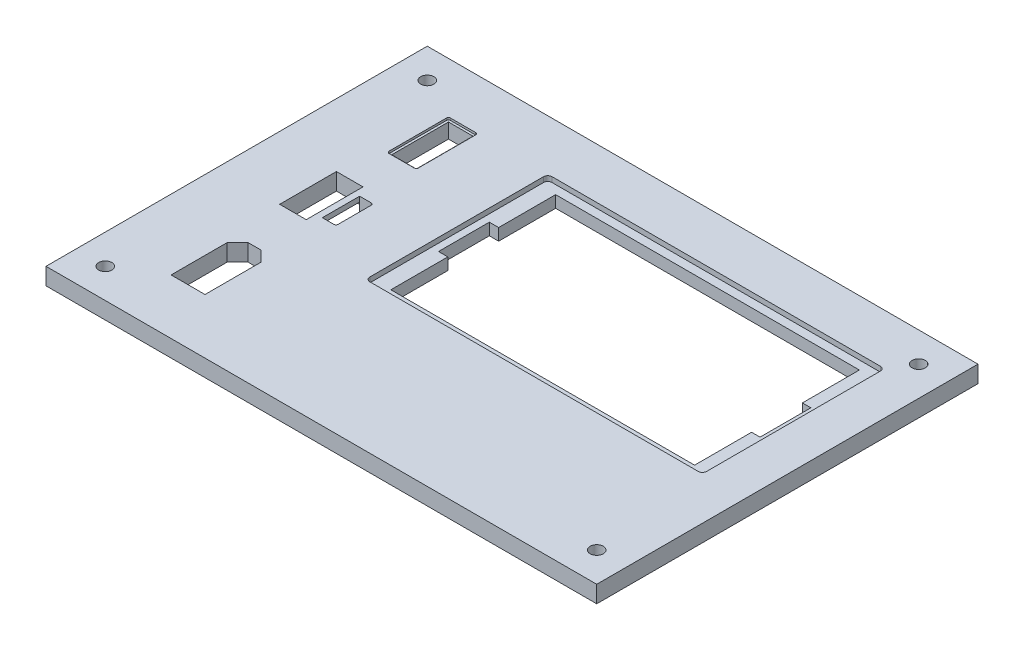
SolidWorks part; units mm, degrees
ref_plane "Спереди" through (0, 0, 0) normal (0, 0, 1) x (1, 0, 0)
ref_plane "Сверху" through (0, 0, 0) normal (0, 1, 0) x (1, 0, 0)
ref_plane "Справа" through (0, 0, 0) normal (1, 0, 0) x (0, 0, -1)
sketch "Эскиз1" plane through (0, 0, 0) normal (0, 1, 0) x (1, 0, 0)
  line L1 (-65, 45) -> (65, 45)
  line L2 (-65, 45) -> (-65, -45)
  line L3 (-65, -45) -> (65, -45)
  line L4 (65, 45) -> (65, -45)
  line L5 (-65, 45) -> (65, -45) construction
  line L6 (-65, -45) -> (65, 45) construction
  line L7 (-20.7, 31) -> (51, 31)
  line L8 (-20.7, 31) -> (-20.7, -7.9)
  line L9 (-20.7, -7.9) -> (51, -7.9)
  line L10 (51, 31) -> (51, -7.9)
  line L11 (-20.7, 31) -> (51, -7.9) construction
  line L12 (-20.7, -7.9) -> (51, 31) construction
  point P0 (0, 0)
  point P6 (15.15, 11.55)
  dimension "D1" = 130
  dimension "D2" = 90
  dimension "D3" = 71.7
  dimension "D4" = 38.9
  dimension "D5" = 14
  dimension "D6" = 14
extrude "основа" add sketch "Эскиз1" along normal blind 4
sketch "Эскиз2" plane through (0, 4, 0) normal (0, 1, 0) x (1, 0, 0)
  line L0 (51, 31) -> (-20.7, 31) construction
  line L1 (-23.6, 33.05) -> (53.9, 33.05)
  line L2 (-24.6, 32.05) -> (-24.6, -8.95)
  line L3 (-23.6, -9.95) -> (53.9, -9.95)
  line L4 (54.9, 32.05) -> (54.9, -8.95)
  line L5 (-24.6, 33.05) -> (54.9, -9.95) construction
  line L6 (-24.6, -9.95) -> (54.9, 33.05) construction
  line L7 (-20.7, 31) -> (-20.7, -7.9) construction
  arc A0 (53.9, -9.95) -> (54.9, -8.95) centre (53.9, -8.95) ccw
  arc A1 (-24.6, -8.95) -> (-23.6, -9.95) centre (-23.6, -8.95) ccw
  arc A2 (53.9, 33.05) -> (54.9, 32.05) centre (53.9, 32.05) cw
  arc A3 (-23.6, 33.05) -> (-24.6, 32.05) centre (-23.6, 32.05) ccw
  point P0 (15.15, 11.55)
  point P5 (15.15, 33.05)
  point P8 (15.15, 31)
  point P11 (-20.7, 11.55)
  point P12 (-24.6, 11.55)
  dimension "D3" = 1
  dimension "D1" = 79.5
  dimension "D2" = 43
extrude "рамка модуля" cut sketch "Эскиз2" against normal blind 1.2
sketch "Эскиз3" plane through (0, 4, 0) normal (0, 1, 0) x (1, 0, 0)
  line L0 (-50.1, -4.75) -> (-50.1, 8.65)
  line L1 (-47.5, 32.5) -> (-41.7, 32.5)
  line L2 (-47.5, 32.5) -> (-47.5, 19.1)
  line L3 (-47.5, 19.1) -> (-41.7, 19.1)
  line L4 (-41.7, 32.5) -> (-41.7, 19.1)
  line L5 (-47.5, 32.5) -> (-41.7, 19.1) construction
  line L6 (-47.5, 19.1) -> (-41.7, 32.5) construction
  line L7 (-50.1, 8.65) -> (-43.7, 8.65)
  line L8 (-43.7, 8.65) -> (-43.7, 11.1)
  line L9 (-43.7, 11.1) -> (-42.4, 11.1)
  line L10 (-42.4, 11.1) -> (-42.4, 6.35)
  line L11 (-42.4, 6.35) -> (-39.6, 6.35)
  line L12 (-39.1, 5.85) -> (-39.1, -1.95)
  line L13 (-39.6, -2.45) -> (-42.5, -2.45)
  line L14 (-42.5, -2.45) -> (-42.5, -7.2)
  line L15 (-42.5, -7.2) -> (-43.8, -7.2)
  line L16 (-43.8, -7.2) -> (-43.8, -4.75)
  line L17 (-43.8, -4.75) -> (-50.1, -4.75)
  line L18 (-65, 45) -> (-65, -45) construction
  line L19 (-24.6, 32.05) -> (-24.6, -8.95) construction
  line L20 (65, 45) -> (-65, 45) construction
  arc A0 (-39.1, -1.95) -> (-39.6, -2.45) centre (-39.6, -1.95) cw
  arc A1 (-39.6, 6.35) -> (-39.1, 5.85) centre (-39.6, 5.85) cw
  point P0 (-44.6, 25.8)
  point P5 (-50.1, 1.95)
  point P18 (-39.1, 1.95)
  point P19 (-43.15, -7.2)
  point P30 (-39.1, -2.45)
  point P33 (-39.1, 6.35)
  dimension "D16" = 0.5
  dimension "D1" = 5.8
  dimension "D2" = 13.4
  dimension "D3" = 13.4
  dimension "D4" = 8.8
  dimension "D5" = 6.4
  dimension "D6" = 1.3
  dimension "D7" = 11
  dimension "D8" = 3.4
  dimension "D9" = 18.3
  dimension "D10" = 2.6
  dimension "D11" = 2.6
  dimension "D12" = 17.5
  dimension "D13" = 17.1
  dimension "D14" = 12.5
  dimension "D15" = 8
extrude "USB оба" cut sketch "Эскиз3" against normal through all
sketch "Эскиз4" plane through (0, 2.8, 0) normal (0, 1, 0) x (1, 0, 0)
  line L0 (-20.7, 31) -> (-20.7, -7.9) construction
  line L1 (-22.9, 17.55) -> (-18.5, 17.55)
  line L2 (-22.9, 17.55) -> (-22.9, 5.55)
  line L3 (-22.9, 5.55) -> (-18.5, 5.55)
  line L4 (-18.5, 17.55) -> (-18.5, 5.55)
  line L5 (-22.9, 17.55) -> (-18.5, 5.55) construction
  line L6 (-22.9, 5.55) -> (-18.5, 17.55) construction
  line L7 (53, 17.55) -> (53, 5.55)
  line L8 (48.6, 17.55) -> (53, 17.55)
  line L9 (48.6, 17.55) -> (48.6, 5.55)
  line L10 (48.6, 5.55) -> (53, 5.55)
  point P0 (-20.7, 11.55)
  dimension "D1" = 4.4
  dimension "D2" = 12
  dimension "D3" = 2
extrude "ушки модуля" cut sketch "Эскиз4" against normal through all
sketch "Эскиз7" plane through (0, 4, 0) normal (0, 1, 0) x (1, 0, 0)
  line L0 (-47.5, 19.1) -> (-41.7, 19.1) construction
  line L1 (-47.55, 33.05) -> (-41.65, 33.05)
  line L2 (-48.05, 32.55) -> (-48.05, 19.05)
  line L3 (-47.55, 18.55) -> (-41.65, 18.55)
  line L4 (-41.15, 32.55) -> (-41.15, 19.05)
  line L5 (-48.05, 33.05) -> (-41.15, 18.55) construction
  line L6 (-48.05, 18.55) -> (-41.15, 33.05) construction
  line L7 (-41.7, 19.1) -> (-41.7, 32.5) construction
  arc A0 (-41.65, 18.55) -> (-41.15, 19.05) centre (-41.65, 19.05) ccw
  arc A1 (-48.05, 19.05) -> (-47.55, 18.55) centre (-47.55, 19.05) ccw
  arc A2 (-41.65, 33.05) -> (-41.15, 32.55) centre (-41.65, 32.55) cw
  arc A3 (-47.55, 33.05) -> (-48.05, 32.55) centre (-47.55, 32.55) ccw
  point P0 (-44.6, 25.8)
  point P5 (-44.6, 33.05)
  point P8 (-44.6, 19.1)
  point P9 (-48.05, 25.8)
  point P12 (-41.7, 25.8)
  dimension "D3" = 0.5
  dimension "D1" = 6.9
  dimension "D2" = 14.5
extrude "рамка USB" cut sketch "Эскиз7" against normal blind 0.5
sketch "Эскиз8" plane through (0, 4, 0) normal (0, 1, 0) x (1, 0, 0)
  line L1 (-43.8197, 11.1723) -> (-42.3197, 11.1723)
  line L2 (-43.8197, 11.1723) -> (-43.8197, -7.3082)
  line L3 (-43.8197, -7.3082) -> (-42.3197, -7.3082)
  line L4 (-42.3197, 11.1723) -> (-42.3197, -7.3082)
  line L5 (-43.8197, 11.1723) -> (-42.3197, -7.3082) construction
  line L6 (-43.8197, -7.3082) -> (-42.3197, 11.1723) construction
  point P0 (-43.25, 2.0042)
  dimension "D1" = 1.5
extrude "перемычка USB" add sketch "Эскиз8" against normal blind 1.2
sketch "Эскиз5" plane through (0, 4, 0) normal (0, 1, 0) x (1, 0, 0)
  line L0 (-48.4687, -32) -> (-40.4687, -32)
  line L1 (-40.4687, -32) -> (-40.4687, -18.8)
  line L2 (-40.4687, -18.8) -> (-42.9518, -16.3)
  line L3 (-42.9518, -16.3) -> (-45.9856, -16.3)
  line L4 (-45.9856, -16.3) -> (-48.4687, -18.8)
  line L5 (-48.4687, -18.8) -> (-48.4687, -32)
  line L7 (-65, -45) -> (65, -45) construction
  dimension "D1" = 15.7
  dimension "D2" = 8
  dimension "D3" = 2.5
  dimension "D4" = 13
  dimension "D5" = 9.2
extrude "XT60" cut sketch "Эскиз5" against normal through all
sketch "Эскиз9" plane through (0, 4, 0) normal (0, 1, 0) x (1, 0, 0)
  line L0 (65, 45) -> (-65, 45) construction
  line L1 (-65, 45) -> (-65, -45) construction
  line L2 (-58, 38) -> (58, 38) construction
  line L3 (-65, -45) -> (65, -45) construction
  line L4 (65, -45) -> (65, 45) construction
  circle A0 centre (-58, 38) radius 1.55
  circle A1 centre (58, 38) radius 1.55
  circle A2 centre (-58, -38) radius 1.55
  circle A3 centre (58, -38) radius 1.55
  dimension "D1" = 3.1
  dimension "D2" = 7
  dimension "D3" = 7
  dimension "D6" = 116
  dimension "D7" = 7
  dimension "D8" = 7
  dimension "D9" = 7
  dimension "D10" = 7
  dimension "D11" = 7
  dimension "D12" = 7
  dimension "D4" = 2
  dimension "D5" = 2
extrude "Вырез-Вытянуть6" cut sketch "Эскиз9" against normal through all
